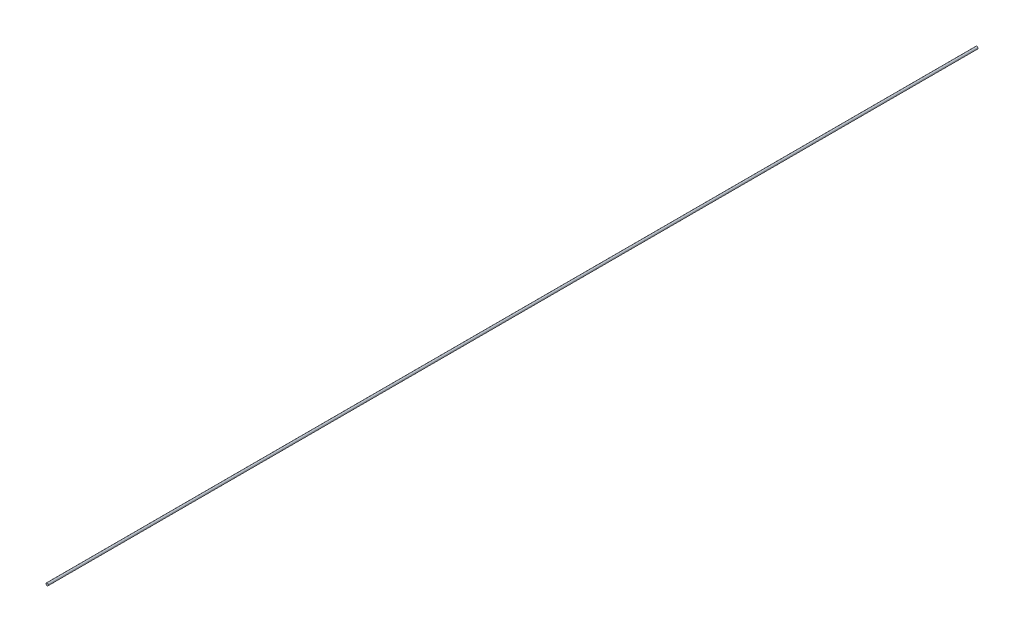
SolidWorks part; units mm, degrees
material "201 Acier inoxydable recuit (SS)"
ref_plane "Plan de face" through (0, 0, 0) normal (0, 0, 1) x (1, 0, 0)
ref_plane "Plan de dessus" through (0, 0, 0) normal (0, 1, 0) x (1, 0, 0)
ref_plane "Plan de droite" through (0, 0, 0) normal (1, 0, 0) x (0, 0, -1)
sketch "Esquisse1" plane through (0, 0, 0) normal (0, 0, 1) x (1, 0, 0)
  circle A0 centre (0, 0) radius 0.5
  dimension "D1" = 1
extrude "Boss.-Extru.1" add sketch "Esquisse1" along normal blind 400
